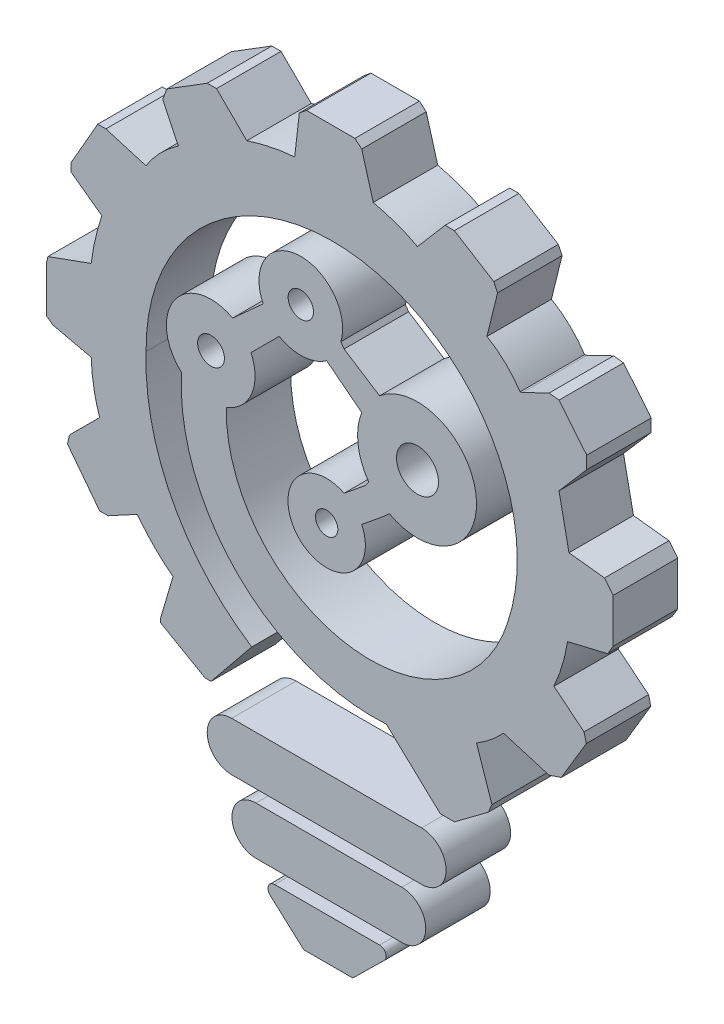
SolidWorks part; units mm, degrees
ref_plane "Front Plane" through (0, 0, 0) normal (0, 0, 1) x (1, 0, 0)
ref_plane "Top Plane" through (0, 0, 0) normal (0, 1, 0) x (1, 0, 0)
ref_plane "Right Plane" through (0, 0, 0) normal (1, 0, 0) x (0, 0, -1)
sketch "Sketch1" plane through (0, 0, 0) normal (0, 0, 1) x (1, 0, 0)
  line L0 (30.4571, 56.7891) -> (92.9051, 56.7891) construction
  line L1 (36.6127, 46.336) -> (66.0639, 46.336) construction
  line L8 (36.6127, 50.1281) -> (66.0639, 50.1281)
  line L11 (36.6127, 42.5438) -> (66.0639, 42.5438)
  line L12 (40.3711, 36.92) -> (62.9922, 36.92) construction
  line L15 (40.3711, 40.6319) -> (62.9922, 40.6319)
  line L16 (40.3711, 33.2082) -> (62.9922, 33.2082)
  line L17 (43.2916, 31.1455) -> (59.5488, 31.1455)
  line L20 (47.7936, 24.6426) -> (55.3803, 24.6426)
  line L21 (60.2553, 29.4313) -> (55.3803, 24.6426)
  line L22 (42.5548, 29.3665) -> (47.7936, 24.6426)
  line L23 (54.0424, 89.0572) -> (57.3383, 91.7453)
  line L24 (56.7754, 86.2384) -> (60.0907, 88.9424)
  line L25 (61.0672, 89.823) -> (60.0907, 88.9424)
  line L26 (57.8581, 92.482) -> (57.3383, 91.7453)
  line L27 (56.7753, 101.2636) -> (51.3382, 105.5029)
  line L28 (59.5486, 104.8905) -> (54.0422, 108.4233)
  line L29 (54.0422, 108.4233) -> (53.5429, 109.1547)
  line L30 (41.4931, 108.2048) -> (36.7513, 103.9283)
  line L31 (43.9752, 105.087) -> (39.6194, 100.7312)
  line L32 (60.5789, 61.3321) -> (68.9548, 53.4849)
  line L33 (71.1414, 53.4849) -> (76.4211, 57.4313)
  line L34 (76.4211, 57.4313) -> (76.9544, 58.7112)
  line L35 (68.9548, 53.4849) -> (71.1414, 53.4849)
  line L36 (76.9544, 58.7112) -> (74.5729, 65.7776)
  line L38 (78.7757, 69.2055) -> (85.8154, 67.0935)
  line L39 (85.8154, 67.0935) -> (87.7229, 67.7364)
  line L40 (87.7229, 67.7364) -> (91.598, 74.2278)
  line L41 (91.598, 74.2278) -> (91.2456, 75.6243)
  line L42 (91.2456, 75.6243) -> (86.565, 79.3976)
  line L44 (88.6833, 86.4585) -> (94.9099, 87.9467)
  line L45 (94.9099, 87.9467) -> (95.7671, 89.3827)
  line L46 (95.7671, 89.3827) -> (95.7671, 96.2119)
  line L47 (95.7671, 96.2119) -> (94.413, 97.8721)
  line L48 (94.413, 97.8721) -> (88.9053, 98.5005)
  line L50 (87.3603, 106.0456) -> (91.6591, 111.0252)
  line L51 (91.6591, 111.0252) -> (91.6591, 112.9758)
  line L52 (91.6591, 112.9758) -> (87.3603, 118.2186)
  line L53 (87.3603, 118.2186) -> (85.8154, 118.3949)
  line L54 (85.8154, 118.3949) -> (81.6957, 116.4107)
  line L55 (81.6957, 116.4107) -> (81.3263, 116.3111)
  line L56 (76.183, 121.1698) -> (77.8389, 127.8606)
  line L57 (77.8389, 127.8606) -> (77.2534, 129.0763)
  line L58 (77.2534, 129.0763) -> (71.1414, 132.8624)
  line L59 (71.1414, 132.8624) -> (69.7035, 132.8624)
  line L60 (69.7035, 132.8624) -> (65.4214, 127.8606)
  line L62 (58.5608, 130.3615) -> (56.7753, 136.6375)
  line L63 (56.7753, 136.6375) -> (55.7168, 137.5437)
  line L64 (55.7168, 137.5437) -> (48.205, 137.5437)
  line L65 (48.205, 137.5437) -> (47.0998, 136.6375)
  line L66 (47.0998, 136.6375) -> (46.3837, 130.3615)
  line L68 (38.9609, 128.8416) -> (34.2686, 133.4995)
  line L69 (34.2686, 133.4995) -> (32.8354, 133.4995)
  line L70 (32.8354, 133.4995) -> (26.5591, 129.6015)
  line L71 (26.5591, 129.6015) -> (25.9244, 127.8606)
  line L72 (25.9244, 127.8606) -> (28.3434, 122.8381)
  line L74 (23.3503, 117.6686) -> (17.1161, 119.5092)
  line L75 (17.1161, 119.5092) -> (15.8505, 119.5092)
  line L76 (15.8505, 119.5092) -> (11.7019, 112.2544)
  line L77 (11.7019, 112.2544) -> (11.7019, 111.0252)
  line L78 (11.7019, 111.0252) -> (16.4833, 107.5433)
  line L80 (14.8364, 100.3097) -> (8.1201, 97.8723)
  line L81 (8.1201, 97.8723) -> (7.8723, 96.7838)
  line L82 (7.8723, 96.7838) -> (7.8723, 89.823)
  line L83 (7.8723, 89.823) -> (8.924, 89.0572)
  line L84 (8.924, 89.0572) -> (14.8364, 87.7111)
  line L86 (16.1477, 80.2776) -> (11.4783, 75.6082)
  line L87 (11.4783, 75.6082) -> (11.164, 74.2278)
  line L88 (11.164, 74.2278) -> (16.1477, 67.7364)
  line L89 (16.1477, 67.7364) -> (17.4483, 67.7364)
  line L90 (17.4483, 67.7364) -> (21.968, 70.1863)
  line L92 (27.5295, 64.6248) -> (25.6004, 58.0911)
  line L93 (25.6004, 58.0911) -> (25.6004, 57.4313)
  line L94 (25.6004, 57.4313) -> (32.5018, 53.4849)
  line L95 (32.5018, 53.4849) -> (33.4122, 53.4849)
  line L96 (33.4122, 53.4849) -> (39.7262, 61.2639)
  arc A4 (36.6127, 50.1281) -> (36.6127, 42.5438) centre (36.6127, 46.336) ccw
  arc A5 (66.0639, 42.5438) -> (66.0639, 50.1281) centre (66.0639, 46.336) ccw
  arc A8 (40.3711, 40.6319) -> (40.3711, 33.2082) centre (40.3711, 36.92) ccw
  arc A9 (62.9922, 33.2082) -> (62.9922, 40.6319) centre (62.9922, 36.92) ccw
  arc A12 (60.2553, 29.4313) -> (59.5488, 31.1455) centre (59.5542, 30.145) ccw
  arc A13 (43.2916, 31.1455) -> (42.5548, 29.3665) centre (43.2916, 30.1034) ccw
  circle A14 centre (51.3383, 83.7011) radius 1.7357
  arc A16 (54.0424, 89.0572) -> (56.7754, 86.2384) centre (51.3383, 83.7011) ccw
  circle A17 centre (65.4214, 97.8721) radius 3.2539
  arc A18 (59.5486, 104.8905) -> (61.0672, 89.823) centre (65.4214, 97.8721) cw
  arc A19 (56.7753, 101.2636) -> (57.8581, 92.482) centre (65.4214, 97.8721) ccw
  circle A20 centre (47.3331, 111.0252) radius 1.9632
  arc A21 (53.5429, 109.1547) -> (41.4931, 108.2048) centre (47.3331, 111.0252) ccw
  arc A22 (51.3382, 105.5029) -> (43.9752, 105.087) centre (47.3331, 111.0252) cw
  circle A23 centre (33.4122, 97.8723) radius 2.0772
  arc A24 (36.7513, 103.9283) -> (28.8345, 92.6889) centre (33.4122, 97.8723) ccw
  arc A25 (39.6194, 100.7312) -> (35.7806, 91.462) centre (33.4122, 97.8723) cw
  arc A26 (28.8345, 92.6889) -> (60.5789, 61.3321) centre (58.5608, 91.0359) ccw
  arc A27 (35.7806, 91.462) -> (79.3675, 84.2956) centre (58.0912, 91.0243) ccw
  arc A28 (79.3675, 84.2956) -> (63.999, 119.5092) centre (52.423, 93.4965) ccw
  arc A29 (63.999, 119.5092) -> (23.3503, 92.7292) centre (52.2487, 93.1048) ccw
  arc A30 (39.7262, 61.2639) -> (23.3503, 92.7292) centre (59.3064, 91.4483) cw
  arc A33 (16.4833, 107.5433) -> (14.8364, 100.3097) centre (52.4804, 95.5437) ccw
  spline S0 degree 2 poles (14.8364, 87.7111) (14.97, 83.7216) (16.1477, 80.2776) knots 0 0 0 1 1 1
  spline S1 degree 2 poles (27.5295, 64.6248) (24.5135, 66.8639) (21.968, 70.1863) knots 0 0 0 1 1 1
  spline S2 degree 2 poles (28.3434, 122.8381) (25.0832, 120.5414) (23.3503, 117.6686) knots 0 0 0 1 1 1
  spline S3 degree 2 poles (46.3837, 130.3615) (43.2077, 130.1934) (38.9609, 128.8416) knots 0 0 0 1 1 1
  spline S4 degree 2 poles (65.4214, 127.8606) (62.7623, 129.3468) (58.5608, 130.3615) knots 0 0 0 1 1 1
  spline S5 degree 2 poles (76.183, 121.1698) (79.2538, 119.4133) (81.3263, 116.3111) knots 0 0 0 1 1 1
  spline S6 degree 1 poles (87.3603, 106.0456) (88.9053, 98.5005) knots 0 0 1 1
  spline S7 degree 2 poles (88.6833, 86.4585) (88.1006, 82.7484) (86.565, 79.3976) knots 0 0 0 1 1 1
  spline S8 degree 2 poles (78.7757, 69.2055) (76.889, 67.188) (74.5729, 65.7776) knots 0 0 0 1 1 1
  point P4 (51.3383, 46.336)
  point P12 (51.6817, 36.92)
extrude "Boss-Extrude1" add sketch "Sketch1" along normal blind 10
sketch "Sketch2" plane through (0, 0, 0) normal (0, 0, -1) x (-1, 0, 0)
  line L1 (-54.14, 86.5559) -> (-58.8145, 90.3685)
  line L2 (-58.8145, 90.3685) -> (-60.3896, 92.6007)
  line L3 (-59.3021, 101.8295) -> (-51.2009, 108.146)
  line L4 (-43.8018, 107.742) -> (-37.0804, 101.0206)
  line L5 (-36.8123, 60.8475) -> (-32.6415, 55.7089)
  line L6 (-32.6415, 55.7089) -> (-32.6415, 55.7089)
  line L7 (-32.6415, 55.7089) -> (-27.7999, 58.4775)
  line L8 (-27.7999, 58.4775) -> (-27.7999, 58.4775)
  line L9 (-27.7999, 58.4775) -> (-29.8561, 65.442)
  line L10 (-22.5558, 72.7799) -> (-17.077, 69.8101)
  line L11 (-17.077, 69.8101) -> (-17.077, 69.8101)
  line L12 (-17.077, 69.8101) -> (-13.3557, 74.6573)
  line L13 (-13.3557, 74.6573) -> (-13.3557, 74.6573)
  line L14 (-13.3557, 74.6573) -> (-18.4724, 79.7739)
  line L15 (-16.8248, 89.3096) -> (-9.8723, 90.8925)
  line L16 (-9.8723, 90.8925) -> (-9.8723, 90.8925)
  line L17 (-9.8723, 90.8925) -> (-9.8723, 96.3806)
  line L18 (-9.8723, 96.3806) -> (-9.8723, 96.3806)
  line L19 (-9.8723, 96.3806) -> (-16.6887, 98.8543)
  line L20 (-18.8683, 108.2807) -> (-13.8311, 111.9488)
  line L21 (-13.8311, 111.9488) -> (-13.8311, 111.9488)
  line L22 (-13.8311, 111.9488) -> (-16.9842, 117.4628)
  line L23 (-16.9842, 117.4628) -> (-16.9842, 117.4628)
  line L24 (-16.9842, 117.4628) -> (-24.3628, 115.2843)
  line L25 (-30.9081, 122.1222) -> (-28.0924, 127.9683)
  line L26 (-28.0924, 127.9683) -> (-28.2014, 128.2672)
  line L27 (-28.2014, 128.2672) -> (-33.4059, 131.4995)
  line L28 (-33.4059, 131.4995) -> (-33.4444, 131.4995)
  line L29 (-33.4444, 131.4995) -> (-38.424, 126.5564)
  line L30 (-48.1674, 128.3526) -> (-48.988, 135.5437)
  line L31 (-48.988, 135.5437) -> (-48.988, 135.5437)
  line L32 (-48.988, 135.5437) -> (-54.9776, 135.5437)
  line L33 (-54.9776, 135.5437) -> (-55.0166, 135.5103)
  line L34 (-55.0166, 135.5103) -> (-56.9612, 128.6751)
  line L35 (-65.8037, 125.2318) -> (-70.6061, 130.8413)
  line L36 (-70.6061, 130.8413) -> (-70.6061, 130.8413)
  line L37 (-70.6061, 130.8413) -> (-75.7045, 127.6831)
  line L38 (-75.7045, 127.6831) -> (-75.7244, 127.6418)
  line L39 (-75.7244, 127.6418) -> (-73.8578, 120.0996)
  line L40 (-80.3979, 113.9894) -> (-82.3959, 114.5281)
  line L41 (-82.3959, 114.5281) -> (-86.1627, 116.3423)
  line L42 (-86.1627, 116.3423) -> (-86.3279, 116.3234)
  line L43 (-86.3279, 116.3234) -> (-89.6591, 112.2607)
  line L44 (-89.6591, 112.2607) -> (-89.6591, 111.769)
  line L45 (-89.6591, 111.769) -> (-85.2037, 106.608)
  line L46 (-85.2037, 106.608) -> (-87.237, 96.6779)
  line L47 (-87.237, 96.6779) -> (-93.3776, 95.9772)
  line L48 (-93.3776, 95.9772) -> (-93.7671, 95.4997)
  line L49 (-93.7671, 95.4997) -> (-93.7671, 89.9342)
  line L50 (-93.7671, 89.9342) -> (-93.6248, 89.6959)
  line L51 (-93.6248, 89.6959) -> (-86.8806, 88.0839)
  line L52 (-84.0603, 78.8479) -> (-89.4385, 74.5121)
  line L53 (-89.4385, 74.5121) -> (-89.4385, 74.5121)
  line L54 (-89.4385, 74.5121) -> (-86.3843, 69.3958)
  line L55 (-86.3843, 69.3958) -> (-85.7801, 69.1922)
  line L56 (-85.7801, 69.1922) -> (-78.1209, 71.49)
  line L57 (-72.1441, 66.722) -> (-74.8187, 58.7857)
  line L58 (-74.8187, 58.7857) -> (-74.7854, 58.7056)
  line L59 (-74.7854, 58.7056) -> (-70.4765, 55.4849)
  line L60 (-70.4765, 55.4849) -> (-69.7453, 55.4849)
  line L61 (-69.7453, 55.4849) -> (-61.2981, 63.3988)
  line L62 (-36.8826, 101.3536) -> (-44.1277, 107.8876)
  line L63 (-51.2885, 108.91) -> (-52.6198, 106.9596)
  line L64 (-52.6198, 106.9596) -> (-59.8316, 102.3327)
  line L65 (-60.8803, 92.3476) -> (-58.7881, 90.4609)
  line L66 (-58.7881, 90.4609) -> (-54.0759, 86.6175)
  line L67 (-54.0424, 89.0572) -> (-57.3383, 91.7453)
  line L68 (-57.3383, 91.7453) -> (-57.8581, 92.482)
  line L69 (-56.7753, 101.2636) -> (-51.3382, 105.5029)
  line L70 (-43.9752, 105.087) -> (-39.6194, 100.7312)
  line L71 (-39.7262, 61.2639) -> (-33.4122, 53.4849)
  line L72 (-33.4122, 53.4849) -> (-32.5018, 53.4849)
  line L73 (-32.5018, 53.4849) -> (-25.6004, 57.4313)
  line L74 (-25.6004, 57.4313) -> (-25.6004, 58.0911)
  line L75 (-25.6004, 58.0911) -> (-27.5295, 64.6248)
  line L76 (-21.968, 70.1863) -> (-17.4483, 67.7364)
  line L77 (-17.4483, 67.7364) -> (-16.1477, 67.7364)
  line L78 (-16.1477, 67.7364) -> (-11.164, 74.2278)
  line L79 (-11.164, 74.2278) -> (-11.4783, 75.6082)
  line L80 (-11.4783, 75.6082) -> (-16.1477, 80.2776)
  line L81 (-14.8364, 87.7111) -> (-8.924, 89.0572)
  line L82 (-8.924, 89.0572) -> (-7.8723, 89.823)
  line L83 (-7.8723, 89.823) -> (-7.8723, 96.7838)
  line L84 (-7.8723, 96.7838) -> (-8.1201, 97.8723)
  line L85 (-8.1201, 97.8723) -> (-14.8364, 100.3097)
  line L86 (-16.4833, 107.5433) -> (-11.7019, 111.0252)
  line L87 (-11.7019, 111.0252) -> (-11.7019, 112.2544)
  line L88 (-11.7019, 112.2544) -> (-15.8505, 119.5092)
  line L89 (-15.8505, 119.5092) -> (-17.1161, 119.5092)
  line L90 (-17.1161, 119.5092) -> (-23.3503, 117.6686)
  line L91 (-28.3434, 122.8381) -> (-25.9244, 127.8606)
  line L92 (-25.9244, 127.8606) -> (-26.5591, 129.6015)
  line L93 (-26.5591, 129.6015) -> (-32.8354, 133.4995)
  line L94 (-32.8354, 133.4995) -> (-34.2686, 133.4995)
  line L95 (-34.2686, 133.4995) -> (-38.9609, 128.8416)
  line L96 (-46.3837, 130.3615) -> (-47.0998, 136.6375)
  line L97 (-47.0998, 136.6375) -> (-48.205, 137.5437)
  line L98 (-48.205, 137.5437) -> (-55.7168, 137.5437)
  line L99 (-55.7168, 137.5437) -> (-56.7753, 136.6375)
  line L100 (-56.7753, 136.6375) -> (-58.5608, 130.3615)
  line L101 (-65.4214, 127.8606) -> (-69.7035, 132.8624)
  line L102 (-69.7035, 132.8624) -> (-71.1414, 132.8624)
  line L103 (-71.1414, 132.8624) -> (-77.2534, 129.0763)
  line L104 (-77.2534, 129.0763) -> (-77.8389, 127.8606)
  line L105 (-77.8389, 127.8606) -> (-76.183, 121.1698)
  line L106 (-81.3263, 116.3111) -> (-81.6957, 116.4107)
  line L107 (-81.6957, 116.4107) -> (-85.8154, 118.3949)
  line L108 (-85.8154, 118.3949) -> (-87.3603, 118.2186)
  line L109 (-87.3603, 118.2186) -> (-91.6591, 112.9758)
  line L110 (-91.6591, 112.9758) -> (-91.6591, 111.0252)
  line L111 (-91.6591, 111.0252) -> (-87.3603, 106.0456)
  line L112 (-87.3603, 106.0456) -> (-88.9053, 98.5005)
  line L113 (-88.9053, 98.5005) -> (-94.413, 97.8721)
  line L114 (-94.413, 97.8721) -> (-95.7671, 96.2119)
  line L115 (-95.7671, 96.2119) -> (-95.7671, 89.3827)
  line L116 (-95.7671, 89.3827) -> (-94.9099, 87.9467)
  line L117 (-94.9099, 87.9467) -> (-88.6833, 86.4585)
  line L118 (-86.565, 79.3976) -> (-91.2456, 75.6243)
  line L119 (-91.2456, 75.6243) -> (-91.598, 74.2278)
  line L120 (-91.598, 74.2278) -> (-87.7229, 67.7364)
  line L121 (-87.7229, 67.7364) -> (-85.8154, 67.0935)
  line L122 (-85.8154, 67.0935) -> (-78.7757, 69.2055)
  line L123 (-74.5729, 65.7776) -> (-76.9544, 58.7112)
  line L124 (-76.9544, 58.7112) -> (-76.4211, 57.4313)
  line L125 (-76.4211, 57.4313) -> (-71.1414, 53.4849)
  line L126 (-71.1414, 53.4849) -> (-68.9548, 53.4849)
  line L127 (-68.9548, 53.4849) -> (-60.5789, 61.3321)
  line L128 (-36.7513, 103.9283) -> (-41.4931, 108.2048)
  line L129 (-53.5429, 109.1547) -> (-54.0422, 108.4233)
  line L130 (-54.0422, 108.4233) -> (-59.5486, 104.8905)
  line L131 (-61.0672, 89.823) -> (-60.0907, 88.9424)
  line L132 (-60.0907, 88.9424) -> (-56.7754, 86.2384)
  line L133 (-54.0424, 89.0572) -> (-57.3383, 91.7453)
  line L134 (-57.3383, 91.7453) -> (-57.8581, 92.482)
  line L135 (-56.7753, 101.2636) -> (-51.3382, 105.5029)
  line L136 (-43.9752, 105.087) -> (-39.6194, 100.7312)
  line L137 (-39.7262, 61.2639) -> (-33.4122, 53.4849)
  line L138 (-33.4122, 53.4849) -> (-32.5018, 53.4849)
  line L139 (-32.5018, 53.4849) -> (-25.6004, 57.4313)
  line L140 (-25.6004, 57.4313) -> (-25.6004, 58.0911)
  line L141 (-25.6004, 58.0911) -> (-27.5295, 64.6248)
  line L142 (-21.968, 70.1863) -> (-17.4483, 67.7364)
  line L143 (-17.4483, 67.7364) -> (-16.1477, 67.7364)
  line L144 (-16.1477, 67.7364) -> (-11.164, 74.2278)
  line L145 (-11.164, 74.2278) -> (-11.4783, 75.6082)
  line L146 (-11.4783, 75.6082) -> (-16.1477, 80.2776)
  line L147 (-14.8364, 87.7111) -> (-8.924, 89.0572)
  line L148 (-8.924, 89.0572) -> (-7.8723, 89.823)
  line L149 (-7.8723, 89.823) -> (-7.8723, 96.7838)
  line L150 (-7.8723, 96.7838) -> (-8.1201, 97.8723)
  line L151 (-8.1201, 97.8723) -> (-14.8364, 100.3097)
  line L152 (-16.4833, 107.5433) -> (-11.7019, 111.0252)
  line L153 (-11.7019, 111.0252) -> (-11.7019, 112.2544)
  line L154 (-11.7019, 112.2544) -> (-15.8505, 119.5092)
  line L155 (-15.8505, 119.5092) -> (-17.1161, 119.5092)
  line L156 (-17.1161, 119.5092) -> (-23.3503, 117.6686)
  line L157 (-28.3434, 122.8381) -> (-25.9244, 127.8606)
  line L158 (-25.9244, 127.8606) -> (-26.5591, 129.6015)
  line L159 (-26.5591, 129.6015) -> (-32.8354, 133.4995)
  line L160 (-32.8354, 133.4995) -> (-34.2686, 133.4995)
  line L161 (-34.2686, 133.4995) -> (-38.9609, 128.8416)
  line L162 (-46.3837, 130.3615) -> (-47.0998, 136.6375)
  line L163 (-47.0998, 136.6375) -> (-48.205, 137.5437)
  line L164 (-48.205, 137.5437) -> (-55.7168, 137.5437)
  line L165 (-55.7168, 137.5437) -> (-56.7753, 136.6375)
  line L166 (-56.7753, 136.6375) -> (-58.5608, 130.3615)
  line L167 (-65.4214, 127.8606) -> (-69.7035, 132.8624)
  line L168 (-69.7035, 132.8624) -> (-71.1414, 132.8624)
  line L169 (-71.1414, 132.8624) -> (-77.2534, 129.0763)
  line L170 (-77.2534, 129.0763) -> (-77.8389, 127.8606)
  line L171 (-77.8389, 127.8606) -> (-76.183, 121.1698)
  line L172 (-81.3263, 116.3111) -> (-81.6957, 116.4107)
  line L173 (-81.6957, 116.4107) -> (-85.8154, 118.3949)
  line L174 (-85.8154, 118.3949) -> (-87.3603, 118.2186)
  line L175 (-87.3603, 118.2186) -> (-91.6591, 112.9758)
  line L176 (-91.6591, 112.9758) -> (-91.6591, 111.0252)
  line L177 (-91.6591, 111.0252) -> (-87.3603, 106.0456)
  line L178 (-87.3603, 106.0456) -> (-88.9053, 98.5005)
  line L179 (-88.9053, 98.5005) -> (-94.413, 97.8721)
  line L180 (-94.413, 97.8721) -> (-95.7671, 96.2119)
  line L181 (-95.7671, 96.2119) -> (-95.7671, 89.3827)
  line L182 (-95.7671, 89.3827) -> (-94.9099, 87.9467)
  line L183 (-94.9099, 87.9467) -> (-88.6833, 86.4585)
  line L184 (-86.565, 79.3976) -> (-91.2456, 75.6243)
  line L185 (-91.2456, 75.6243) -> (-91.598, 74.2278)
  line L186 (-91.598, 74.2278) -> (-87.7229, 67.7364)
  line L187 (-87.7229, 67.7364) -> (-85.8154, 67.0935)
  line L188 (-85.8154, 67.0935) -> (-78.7757, 69.2055)
  line L189 (-74.5729, 65.7776) -> (-76.9544, 58.7112)
  line L190 (-76.9544, 58.7112) -> (-76.4211, 57.4313)
  line L191 (-76.4211, 57.4313) -> (-71.1414, 53.4849)
  line L192 (-71.1414, 53.4849) -> (-68.9548, 53.4849)
  line L193 (-68.9548, 53.4849) -> (-60.5789, 61.3321)
  line L194 (-36.7513, 103.9283) -> (-41.4931, 108.2048)
  line L195 (-53.5429, 109.1547) -> (-54.0422, 108.4233)
  line L196 (-54.0422, 108.4233) -> (-59.5486, 104.8905)
  line L197 (-61.0672, 89.823) -> (-60.0907, 88.9424)
  line L198 (-60.0907, 88.9424) -> (-56.7754, 86.2384)
  arc A0 (-54.0759, 86.6175) -> (-54.14, 86.5559) centre (-51.3383, 83.7011) ccw
  arc A1 (-60.3896, 92.6007) -> (-59.3021, 101.8295) centre (-65.4214, 97.8721) ccw
  arc A2 (-51.2009, 108.146) -> (-43.8018, 107.742) centre (-47.3331, 111.0252) ccw
  arc A3 (-37.0804, 101.0206) -> (-33.8616, 93.0594) centre (-33.4122, 97.8723) ccw
  arc A4 (-81.2676, 83.6708) -> (-33.8616, 93.0594) centre (-58.0912, 91.0243) ccw
  arc A5 (-64.8122, 121.3364) -> (-81.2676, 83.6708) centre (-52.423, 93.4965) ccw
  arc A6 (-21.3499, 92.752) -> (-64.8122, 121.3364) centre (-52.2487, 93.1048) ccw
  arc A7 (-36.8123, 60.8475) -> (-21.3499, 92.752) centre (-59.3064, 91.4483) ccw
  arc A8 (-16.6887, 98.8543) -> (-18.8683, 108.2807) centre (-52.4804, 95.5437) ccw
  arc A9 (-61.2981, 63.3988) -> (-30.911, 93.6408) centre (-58.5608, 91.0359) ccw
  arc A10 (-30.911, 93.6408) -> (-36.8826, 101.3536) centre (-33.4122, 97.8723) ccw
  arc A11 (-44.1277, 107.8876) -> (-51.2885, 108.91) centre (-47.3331, 111.0252) ccw
  arc A12 (-59.8316, 102.3327) -> (-60.8803, 92.3476) centre (-65.4214, 97.8721) ccw
  arc A13 (-56.7754, 86.2384) -> (-54.0424, 89.0572) centre (-51.3383, 83.7011) ccw
  arc A14 (-57.8581, 92.482) -> (-56.7753, 101.2636) centre (-65.4214, 97.8721) ccw
  arc A15 (-51.3382, 105.5029) -> (-43.9752, 105.087) centre (-47.3331, 111.0252) ccw
  arc A16 (-39.6194, 100.7312) -> (-35.7806, 91.462) centre (-33.4122, 97.8723) ccw
  arc A17 (-79.3675, 84.2956) -> (-35.7806, 91.462) centre (-58.0912, 91.0243) ccw
  arc A18 (-63.999, 119.5092) -> (-79.3675, 84.2956) centre (-52.423, 93.4965) ccw
  arc A19 (-23.3503, 92.7292) -> (-63.999, 119.5092) centre (-52.2487, 93.1048) ccw
  arc A20 (-39.7262, 61.2639) -> (-23.3503, 92.7292) centre (-59.3064, 91.4483) ccw
  arc A21 (-14.8364, 100.3097) -> (-16.4833, 107.5433) centre (-52.4804, 95.5437) ccw
  arc A22 (-60.5789, 61.3321) -> (-28.8345, 92.6889) centre (-58.5608, 91.0359) ccw
  arc A23 (-28.8345, 92.6889) -> (-36.7513, 103.9283) centre (-33.4122, 97.8723) ccw
  arc A24 (-41.4931, 108.2048) -> (-53.5429, 109.1547) centre (-47.3331, 111.0252) ccw
  arc A25 (-59.5486, 104.8905) -> (-61.0672, 89.823) centre (-65.4214, 97.8721) ccw
  arc A26 (-56.7754, 86.2384) -> (-54.0424, 89.0572) centre (-51.3383, 83.7011) ccw
  arc A27 (-57.8581, 92.482) -> (-56.7753, 101.2636) centre (-65.4214, 97.8721) ccw
  arc A28 (-51.3382, 105.5029) -> (-43.9752, 105.087) centre (-47.3331, 111.0252) ccw
  arc A29 (-39.6194, 100.7312) -> (-35.7806, 91.462) centre (-33.4122, 97.8723) ccw
  arc A30 (-79.3675, 84.2956) -> (-35.7806, 91.462) centre (-58.0912, 91.0243) ccw
  arc A31 (-63.999, 119.5092) -> (-79.3675, 84.2956) centre (-52.423, 93.4965) ccw
  arc A32 (-23.3503, 92.7292) -> (-63.999, 119.5092) centre (-52.2487, 93.1048) ccw
  arc A33 (-39.7262, 61.2639) -> (-23.3503, 92.7292) centre (-59.3064, 91.4483) ccw
  arc A34 (-14.8364, 100.3097) -> (-16.4833, 107.5433) centre (-52.4804, 95.5437) ccw
  arc A35 (-60.5789, 61.3321) -> (-28.8345, 92.6889) centre (-58.5608, 91.0359) ccw
  arc A36 (-28.8345, 92.6889) -> (-36.7513, 103.9283) centre (-33.4122, 97.8723) ccw
  arc A37 (-41.4931, 108.2048) -> (-53.5429, 109.1547) centre (-47.3331, 111.0252) ccw
  arc A38 (-59.5486, 104.8905) -> (-61.0672, 89.823) centre (-65.4214, 97.8721) ccw
  parabola Q8 (-27.5295, 64.6248) -> (-21.968, 70.1863) focus (-36.6411, 72.3496) apex (-32.1285, 61.957)
  parabola Q9 (-16.1477, 80.2776) -> (-14.8364, 87.7111) focus (-27.2163, 82.2633) apex (-17.4778, 77.1751)
  parabola Q10 (-23.3503, 117.6686) -> (-28.3434, 122.8381) focus (-28.5124, 113.0969) apex (-22.2722, 115.4509)
  parabola Q11 (-38.9609, 128.8416) -> (-46.3837, 130.3615) focus (-51.1069, 126.1376) apex (-53.2201, 128.4735)
  parabola Q12 (-58.5608, 130.3615) -> (-65.4214, 127.8606) focus (-66.8713, 122.2923) apex (-69.7381, 123.1689)
  parabola Q13 (-76.183, 121.1698) -> (-81.3263, 116.3111) focus (-73.2684, 114.293) apex (-77.656, 120.2074)
  parabola Q14 (-88.6833, 86.4585) -> (-86.565, 79.3976) focus (-74.8514, 85.7796) apex (-87.2732, 81.0955)
  parabola Q15 (-78.7757, 69.2055) -> (-74.5729, 65.7776) focus (-70.0201, 74.5575) apex (-75.7041, 66.5208)
  parabola Q16 (-27.5295, 64.6248) -> (-21.968, 70.1863) focus (-36.6411, 72.3496) apex (-32.1285, 61.957)
  parabola Q17 (-16.1477, 80.2776) -> (-14.8364, 87.7111) focus (-27.2163, 82.2633) apex (-17.4778, 77.1751)
  parabola Q18 (-23.3503, 117.6686) -> (-28.3434, 122.8381) focus (-28.5124, 113.0969) apex (-22.2722, 115.4509)
  parabola Q19 (-38.9609, 128.8416) -> (-46.3837, 130.3615) focus (-51.1069, 126.1376) apex (-53.2201, 128.4735)
  parabola Q20 (-58.5608, 130.3615) -> (-65.4214, 127.8606) focus (-66.8713, 122.2923) apex (-69.7381, 123.1689)
  parabola Q21 (-76.183, 121.1698) -> (-81.3263, 116.3111) focus (-73.2684, 114.293) apex (-77.656, 120.2074)
  parabola Q22 (-88.6833, 86.4585) -> (-86.565, 79.3976) focus (-74.8514, 85.7796) apex (-87.2732, 81.0955)
  parabola Q23 (-78.7757, 69.2055) -> (-74.5729, 65.7776) focus (-70.0201, 74.5575) apex (-75.7041, 66.5208)
  spline S0 degree 1 poles (-29.8561, 65.442) (-22.5558, 72.7799) knots 0 0 1 1 construction
  spline S1 degree 1 poles (-18.4724, 79.7739) (-16.8248, 89.3096) knots 0 0 1 1 construction
  spline S2 degree 1 poles (-24.3628, 115.2843) (-30.9081, 122.1222) knots 0 0 1 1 construction
  spline S3 degree 1 poles (-38.424, 126.5564) (-48.1674, 128.3526) knots 0 0 1 1 construction
  spline S4 degree 1 poles (-56.9612, 128.6751) (-65.8037, 125.2318) knots 0 0 1 1 construction
  spline S5 degree 1 poles (-73.8578, 120.0996) (-80.3979, 113.9894) knots 0 0 1 1 construction
  spline S6 degree 1 poles (-86.8806, 88.0839) (-84.0603, 78.8479) knots 0 0 1 1 construction
  spline S7 degree 1 poles (-78.1209, 71.49) (-72.1441, 66.722) knots 0 0 1 1 construction
  spline S8 degree 3 poles (-29.8561, 65.442) (-29.1755, 65.884) (-27.8791, 66.8318) (-26.0024, 68.5312) (-24.5199, 70.1696) (-23.3838, 71.612) (-22.8245, 72.3896) (-22.5558, 72.7799) knots 0.500282 0.500282 0.500282 0.500282 0.500475 0.500667 0.500859 0.500955 0.501051 0.501051 0.501051 0.501051
  spline S9 degree 3 poles (-18.4724, 79.7739) (-18.1809, 80.4842) (-17.6821, 81.9251) (-17.1525, 84.2374) (-16.9031, 86.281) (-16.8191, 87.9836) (-16.8164, 88.8707) (-16.8248, 89.3096) knots 0.500153 0.500153 0.500153 0.500153 0.500341 0.50053 0.500718 0.500812 0.500906 0.500906 0.500906 0.500906
  spline S10 degree 3 poles (-24.3628, 115.2843) (-24.6467, 115.9337) (-25.3222, 117.1593) (-26.735, 118.9215) (-28.2635, 120.3079) (-29.6944, 121.3595) (-30.5042, 121.879) (-30.9081, 122.1222) knots 0.500066 0.500066 0.500066 0.500066 0.500305 0.500543 0.500781 0.5009 0.501019 0.501019 0.501019 0.501019
  spline S11 degree 3 poles (-38.424, 126.5564) (-38.9237, 126.7287) (-39.9513, 127.0654) (-41.8435, 127.6142) (-44.0285, 128.1106) (-45.9197, 128.35) (-47.2723, 128.3963) (-47.8625, 128.3756) (-48.1674, 128.3526) knots 0.498389 0.498389 0.498389 0.498389 0.498504 0.498619 0.49885 0.49908 0.499196 0.499311 0.499311 0.499311 0.499311
  spline S12 degree 3 poles (-56.9612, 128.6751) (-57.464, 128.5668) (-58.4903, 128.3285) (-60.3332, 127.8285) (-62.3772, 127.1332) (-64.0252, 126.3705) (-65.1246, 125.7212) (-65.5766, 125.4058) (-65.8037, 125.2318) knots 0.498448 0.498448 0.498448 0.498448 0.498565 0.498681 0.498915 0.499148 0.499264 0.499381 0.499381 0.499381 0.499381
  spline S13 degree 3 poles (-73.8578, 120.0996) (-74.5416, 119.8034) (-75.8747, 119.0902) (-77.5953, 117.7419) (-78.8646, 116.3448) (-79.7724, 115.063) (-80.2001, 114.3485) (-80.3979, 113.9894) knots 0.499683 0.499683 0.499683 0.499683 0.499917 0.500152 0.500386 0.500504 0.500621 0.500621 0.500621 0.500621
  spline S14 degree 3 poles (-86.8806, 88.0839) (-86.7933, 87.2651) (-86.5412, 85.622) (-85.9467, 83.2789) (-85.1338, 81.0177) (-84.4403, 79.5575) (-84.0603, 78.8479) knots 0.499526 0.499526 0.499526 0.499526 0.499705 0.499883 0.500062 0.50024 0.50024 0.50024 0.50024
  spline S15 degree 3 poles (-78.1209, 71.49) (-77.7049, 70.985) (-76.8135, 70.0072) (-75.3833, 68.7382) (-73.837, 67.6345) (-72.7167, 67.0052) (-72.1441, 66.722) knots 0.499572 0.499572 0.499572 0.499572 0.499741 0.49991 0.500078 0.500247 0.500247 0.500247 0.500247
  dimension "D1" = 0
  dimension "D2" = 2
extrude "Cut-Extrude2" cut sketch "Sketch2" against normal blind 3.5 contours L56 S15 L57 L58 L59 L60 L61 A9 A10 L62 L4 A3 A4 A5 A6 A7 L5 L7 L9 S8 L10 L12 L14 S9 L15 L17 L19 A8 L20 L22 L24 S10 L25 L26 L27 L28 L29 S11 L30 L32 L33 L34 S12 L35 L37 L38 L39 S13 L40 L41 L42
